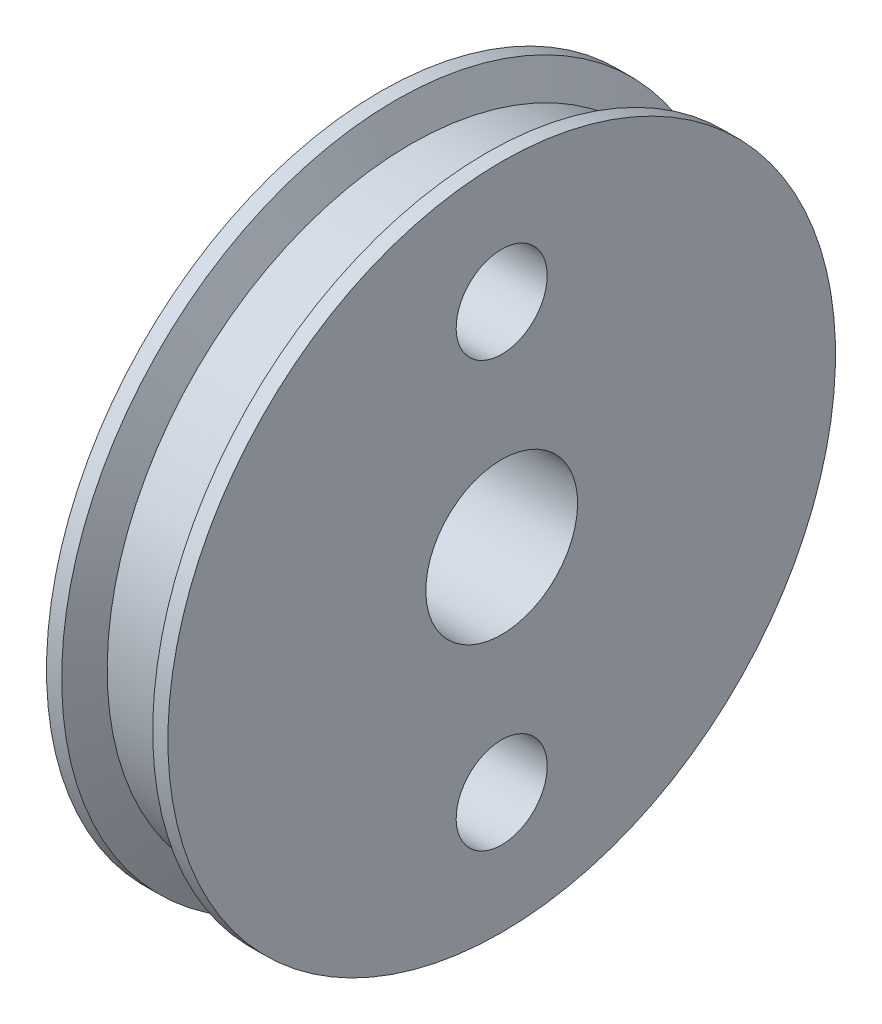
SolidWorks part; units mm, degrees
ref_plane "Plan de face" through (0, 0, 0) normal (0, 0, 1) x (1, 0, 0)
ref_plane "Plan de dessus" through (0, 0, 0) normal (0, 1, 0) x (1, 0, 0)
ref_plane "Plan de droite" through (0, 0, 0) normal (1, 0, 0) x (0, 0, -1)
sketch "Esquisse1" plane through (0, 0, 0) normal (0, 0, 1) x (1, 0, 0)
  line L0 (0, 0) -> (0, 11)
  line L1 (0, 11) -> (0.5, 11)
  line L2 (3.5, 11) -> (4, 11)
  line L3 (4, 11) -> (4, 0)
  line L4 (4, 0) -> (0, 0)
  line L5 (3.5, 11) -> (3, 10)
  line L6 (3, 10) -> (1, 10)
  line L7 (1, 10) -> (0.5, 11)
  line L8 (3, 11) -> (3, 9.5348) construction
  line L9 (3, 9.5348) -> (1, 9.5348) construction
  line L10 (1, 9.5348) -> (1, 11) construction
  point P14 (0, 0)
  point P15 (0, 0)
  dimension "D1" = 11
  dimension "D3" = 1
  dimension "D4" = 1
  dimension "D5" = 1
revolve "Révolution1" add sketch "Esquisse1" angle 360 about L4
sketch "Esquisse2" plane through (4, 0, 0) normal (1, 0, 0) x (0, 0, -1)
  circle A0 centre (0, 0) radius 2.5
  circle A1 centre (0, 7) radius 1.5
  circle A2 centre (0, -7) radius 1.5
  dimension "D1" = 3
  dimension "D2" = 5
  dimension "D3" = 3
  dimension "D4" = 7
  dimension "D5" = 7
extrude "Enlèv. mat.-Extru.1" cut sketch "Esquisse2" against normal blind 10
